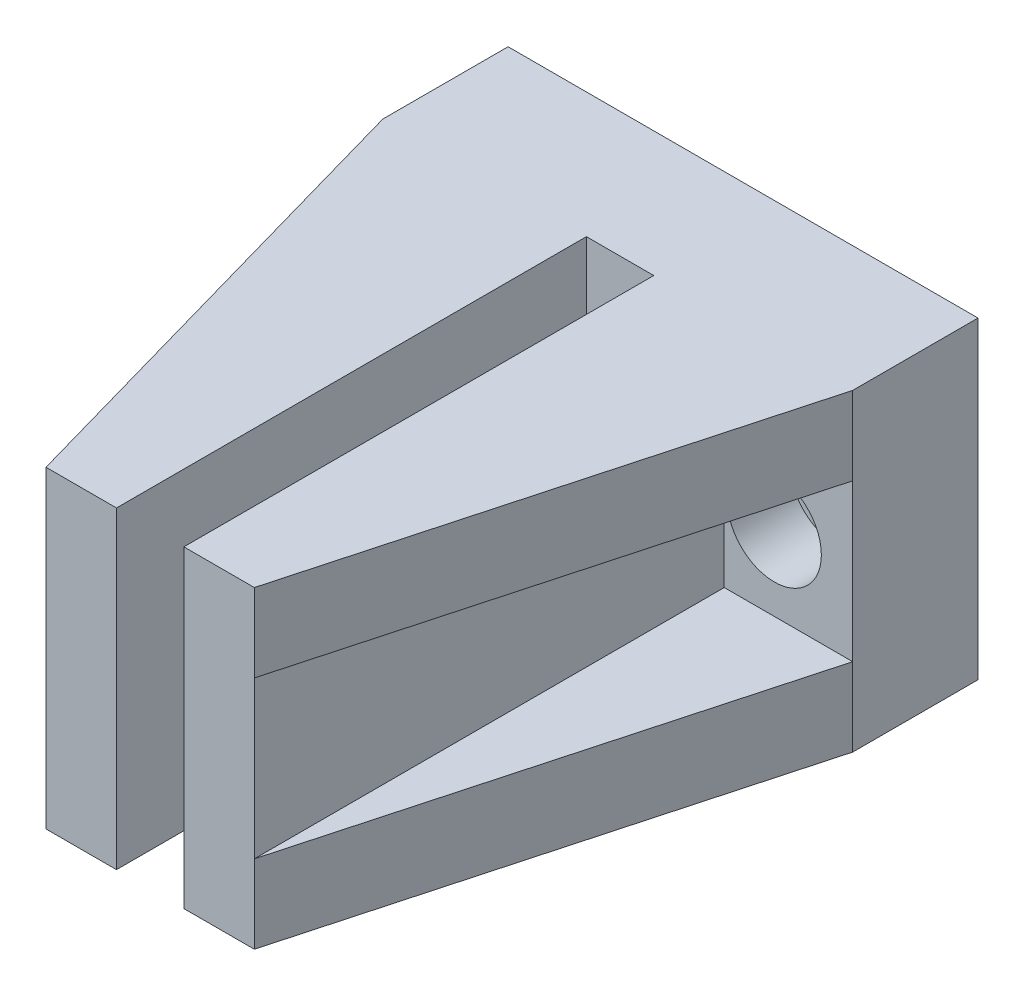
SolidWorks part; units mm, degrees
ref_plane "Front Plane" through (0, 0, 0) normal (0, 0, 1) x (1, 0, 0)
ref_plane "Top Plane" through (0, 0, 0) normal (0, 1, 0) x (1, 0, 0)
ref_plane "Right Plane" through (0, 0, 0) normal (1, 0, 0) x (0, 0, -1)
sketch "Sketch1" plane through (0, 0, 0) normal (0, 0, 1) x (1, 0, 0)
  line L1 (15, -10) -> (-15, -10)
  line L2 (15, -10) -> (15, 10)
  line L3 (15, 10) -> (-15, 10)
  line L4 (-15, -10) -> (-15, 10)
  line L5 (15, -10) -> (-15, 10) construction
  line L6 (15, 10) -> (-15, -10) construction
  circle A0 centre (-10, 0) radius 1.65
  circle A1 centre (9.9998, -0.0942) radius 1.65
  point P0 (0, 0)
  dimension "D4" = 3.3
  dimension "D5" = 5
  dimension "D6" = 10
  dimension "D1" = 20
  dimension "D2" = 30
  dimension "D3" = 20
extrude "Boss-Extrude1" add sketch "Sketch1" along normal blind 8
sketch "Sketch3" plane through (0, 0, 8) normal (0, 0, 1) x (1, 0, 0)
  line L0 (15, 10) -> (-15, 10) construction
  line L1 (-6.5, -10) -> (-2, -10)
  line L2 (-6.5, -10) -> (-6.5, 10)
  line L3 (-6.5, 10) -> (-2, 10)
  line L4 (-2, -10) -> (-2, 10)
  line L5 (-6.5, -10) -> (-2, 10) construction
  line L6 (-6.5, 10) -> (-2, -10) construction
  line L7 (-15, -10) -> (15, -10) construction
  line L8 (2.3, -10) -> (6.8, -10)
  line L9 (2.3, -10) -> (2.3, 10)
  line L10 (2.3, 10) -> (6.8, 10)
  line L11 (6.8, -10) -> (6.8, 10)
  line L12 (2.3, -10) -> (6.8, 10) construction
  line L13 (2.3, 10) -> (6.8, -10) construction
  circle A0 centre (-10, 0) radius 1.65 construction
  point P0 (-4.25, 0)
  point P7 (4.55, 0)
  dimension "D1" = 4.5
  dimension "D2" = 4.5
  dimension "D3" = 4.3
  dimension "D4" = 3.5
extrude "Boss-Extrude2" add sketch "Sketch3" along normal blind 30
sketch "Sketch5" plane through (0, 10, 0) normal (0, 1, 0) x (1, 0, 0)
  line L0 (-15, -8) -> (-6.5, -38)
  line L1 (-6.5, -38) -> (-6.5, -8)
  line L2 (-6.5, -8) -> (-15, -8)
  line L3 (15, -8) -> (6.8, -8)
  line L4 (6.8, -8) -> (6.8, -38)
  line L5 (6.8, -38) -> (15, -8)
extrude "Boss-Extrude3" add sketch "Sketch5" against normal up to surface (20 mm away) up to face at (0.1, -10, 16.6667)
sketch "Sketch6" plane through (0, 0, 38) normal (0, 0, 1) x (1, 0, 0)
  line L0 (-6.5, 10) -> (-6.5, -10) construction
  line L1 (-6.5, 5) -> (-15, 5)
  line L2 (-6.5, 5) -> (-6.5, -5)
  line L3 (-6.5, -5) -> (-15, -5)
  line L4 (-15, 5) -> (-15, -5)
  line L5 (-15, 10) -> (-15, -10) construction
  line L6 (6.8, -10) -> (6.8, 10) construction
  line L7 (6.8, 5) -> (15, 5)
  line L8 (6.8, 5) -> (6.8, -5)
  line L9 (6.8, -5) -> (15, -5)
  line L10 (15, 5) -> (15, -5)
  line L11 (15, -10) -> (15, 10) construction
  line L12 (-15, 10) -> (-6.5, 10) construction
  line L13 (6.8, 10) -> (15, 10) construction
  dimension "D1" = 5
  dimension "D2" = 10
  dimension "D3" = 5
extrude "Cut-Extrude2" cut sketch "Sketch6" against normal up to surface (30 mm away) up to face at (0.15, 0, 8)
sketch "Sketch10" plane through (0, 0, 8) normal (0, 0, 1) x (1, 0, 0)
  circle A0 centre (-10, 0) radius 3
  circle A1 centre (9.9998, -0.0942) radius 3
  dimension "D1" = 6
extrude "Cut-Extrude5" cut sketch "Sketch10" against normal blind 4 contours A0 | A1
